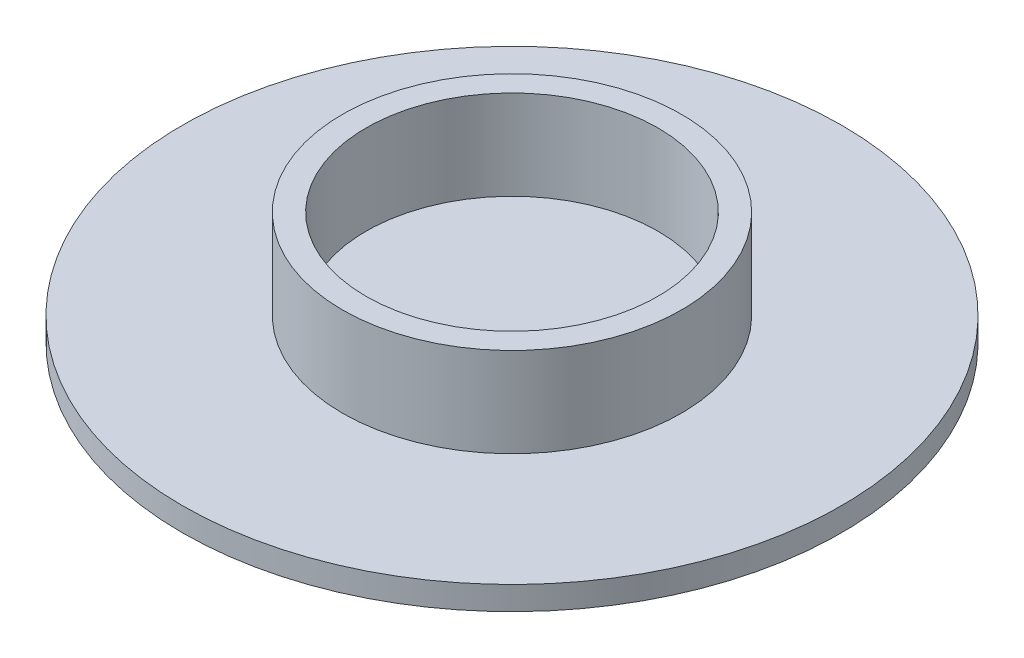
SolidWorks part; units mm, degrees
ref_plane "Front Plane" through (0, 0, 0) normal (0, 0, 1) x (1, 0, 0)
ref_plane "Top Plane" through (0, 0, 0) normal (0, 1, 0) x (1, 0, 0)
ref_plane "Right Plane" through (0, 0, 0) normal (1, 0, 0) x (0, 0, -1)
sketch "Sketch1" plane through (0, 0, 0) normal (1, 0, 0) x (0, 0, -1)
  line L0 (0, 0) -> (70, 0)
  line L1 (70, 0) -> (70, 5)
  line L2 (70, 5) -> (36, 5)
  line L3 (36, 5) -> (36, 24)
  line L4 (36, 24) -> (31, 24)
  line L5 (31, 24) -> (31, 5)
  line L6 (31, 5) -> (0, 5)
  line L7 (0, 5) -> (0, 0)
  dimension "D1" = 5
  dimension "D2" = 36
  dimension "D3" = 70
  dimension "D4" = 5
  dimension "D5" = 19
revolve "Revolve1" add sketch "Sketch1" angle 360 about L7
